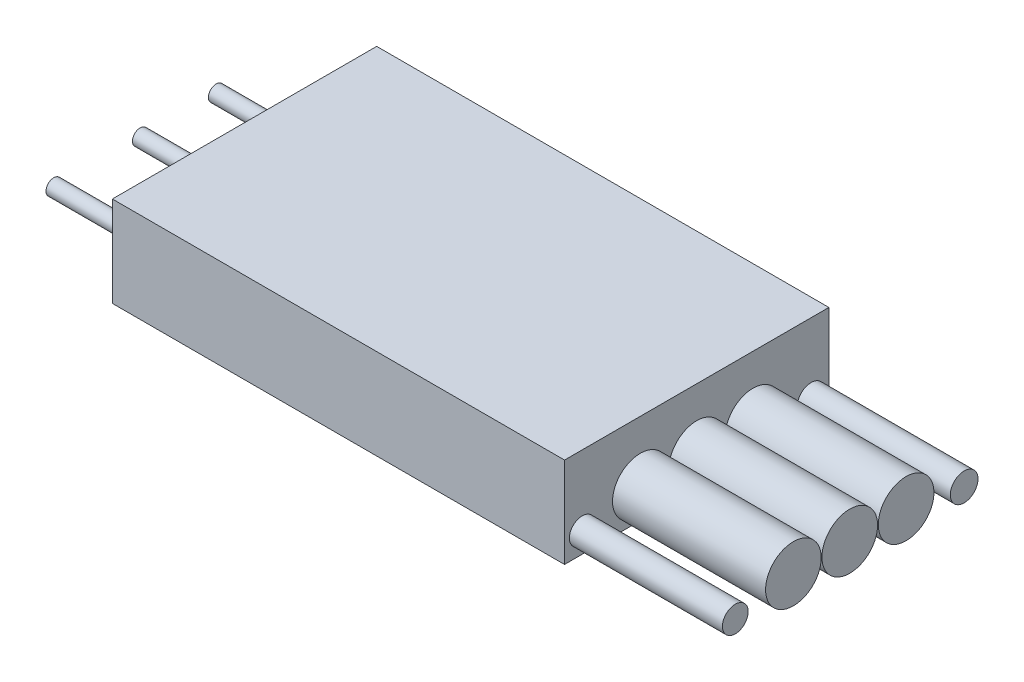
SolidWorks part; units mm, degrees
ref_plane "Front Plane" through (0, 0, 0) normal (0, 0, 1) x (1, 0, 0)
ref_plane "Top Plane" through (0, 0, 0) normal (0, 1, 0) x (1, 0, 0)
ref_plane "Right Plane" through (0, 0, 0) normal (1, 0, 0) x (0, 0, -1)
sketch "Sketch1" plane through (0, 0, 0) normal (1, 0, 0) x (0, 0, -1)
  line L1 (19, 6.5) -> (-19, 6.5)
  line L2 (19, 6.5) -> (19, -6.5)
  line L3 (19, -6.5) -> (-19, -6.5)
  line L4 (-19, 6.5) -> (-19, -6.5)
  line L5 (19, 6.5) -> (-19, -6.5) construction
  line L6 (19, -6.5) -> (-19, 6.5) construction
  point P0 (0, 0)
  dimension "D1" = 13
  dimension "D2" = 38
extrude "Boss-Extrude1" add sketch "Sketch1" along normal blind 65 contours L1 L4 L3 L2
sketch "Sketch2" plane through (65, 0, 0) normal (1, 0, 0) x (0, 0, -1)
  circle A0 centre (0, -2.1007) radius 4
  circle A1 centre (-8.1, -2.1007) radius 4
  circle A2 centre (8.1, -2.1007) radius 4
  circle A3 centre (-16.4553, -3.5646) radius 1.8484
  circle A4 centre (16.4443, -3.5646) radius 1.9915
  point P9 (0, 0)
  dimension "D1" = 8
  dimension "D2" = 8.1
  dimension "D3" = 8.1
extrude "Boss-Extrude4" add sketch "Sketch2" along normal blind 22 contours A3 | A1 | A0 | A2 | A4
sketch "Sketch3" plane through (0, 0, 0) normal (-1, 0, 0) x (0, 0, 1)
  circle A0 centre (-10.9266, -2.7586) radius 1.1186
  circle A1 centre (0, -2.7586) radius 1.1186
  circle A2 centre (12.4202, -2.7586) radius 1.1186
  point P6 (12.4202, -2.7586)
extrude "Boss-Extrude5" add sketch "Sketch3" along normal blind 15
